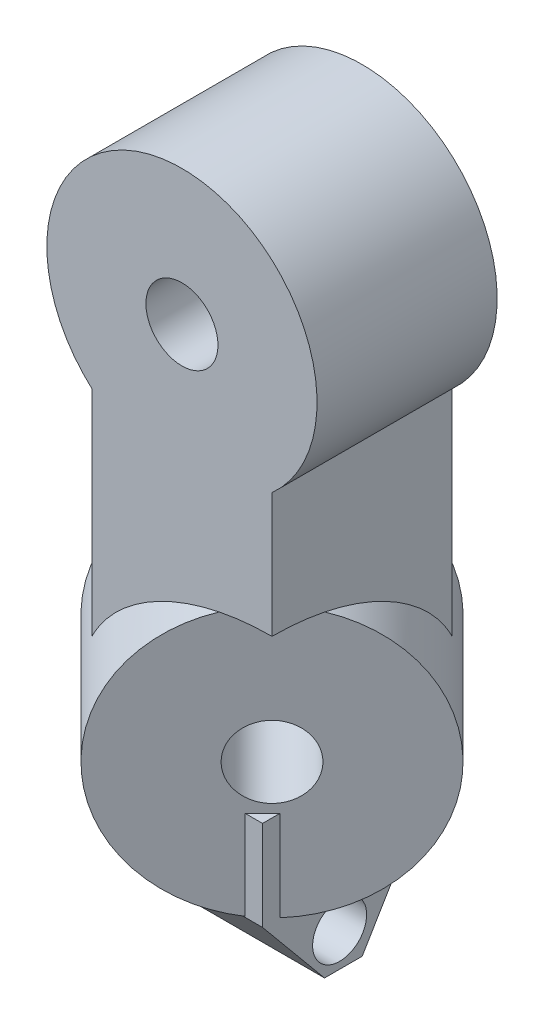
SolidWorks part; units mm, degrees
ref_plane "Front Plane" through (0, 0, 0) normal (0, 0, 1) x (1, 0, 0)
ref_plane "Top Plane" through (0, 0, 0) normal (0, 1, 0) x (1, 0, 0)
ref_plane "Right Plane" through (0, 0, 0) normal (1, 0, 0) x (0, 0, -1)
sketch "Sketch1" plane through (0, 0, 0) normal (0, 0, 1) x (1, 0, 0)
  line L1 (5.0265, -10.0235) -> (-4.9735, -10.0235)
  line L2 (5.0265, -10.0235) -> (5.0265, 4.3863)
  line L4 (-4.9735, -10.0235) -> (-4.9735, 4.3863)
  line L5 (5.0265, -10.0235) -> (-1.3013, 2.5949) construction
  line L6 (1.288, 2.5958) -> (-4.9735, -10.0235) construction
  arc A0 (5.0265, 4.3863) -> (-4.9735, 4.3863) centre (0.0265, 9.9765) ccw
  circle A1 centre (0.0265, 9.9765) radius 1.5
  point P0 (0, 0)
  dimension "D2" = 15
  dimension "D3" = 3
  dimension "D1" = 10
  dimension "D4" = 20
extrude "Boss-Extrude1" add sketch "Sketch1" along normal blind 10
sketch "Sketch2" plane through (0, 0, 0) normal (0, 0, -1) x (-1, 0, 0)
  circle A0 centre (-0.0265, 9.9765) radius 2
  dimension "D1" = 4
extrude "Cut-Extrude1" cut sketch "Sketch2" against normal blind 30 contours A0
ref_plane "Plane1" through (2.5132, 0, 2.5132) normal (-0.7071, 0, -0.7071) x (-0.7071, 0, 0.7071)
sketch "Sketch6" plane through (2.5132, 0, 2.5132) normal (-0.7071, 0, -0.7071) x (-0.7071, 0, 0.7071)
  circle A0 centre (3.5168, -10.0235) radius 7.5
  dimension "D1" = 15
extrude "Boss-Extrude3" add sketch "Sketch6" along normal mid plane 10
sketch "Sketch7" plane through (-1.0223, 0, -1.0223) normal (-0.7071, 0, -0.7071) x (-0.7071, 0, 0.7071)
  line L0 (1.4458, -10.0235) -> (5.5879, -10.0235) construction
  circle A0 centre (3.5168, -10.0235) radius 1.5
  dimension "D1" = 3
extrude "Cut-Extrude4" cut sketch "Sketch7" against normal through all both and the other way through all
sketch "Sketch8" plane through (-1.0223, 0, -1.0223) normal (-0.7071, 0, -0.7071) x (-0.7071, 0, 0.7071)
  circle A0 centre (3.5168, -10.0235) radius 2
  dimension "D1" = 4
extrude "Cut-Extrude5" cut sketch "Sketch8" against normal mid plane 36
sketch "Sketch10" plane through (6.0488, 0, 6.0488) normal (0.7071, 0, 0.7071) x (0.7071, 0, -0.7071)
  circle A0 centre (-3.5168, -10.0235) radius 7.5
extrude "Cut-Extrude7" cut sketch "Sketch10" along normal blind 9
mirror "Mirror1" about plane through (2.5132, 0, 2.5132) normal (-0.7071, 0, -0.7071) of "Cut-Extrude7"
ref_plane "Plane2" through (0, -17.5, 0) normal (0, 1, 0) x (1, 0, 0)
sketch "Sketch11" plane through (0, -17.5, 0) normal (0, 1, 0) x (1, 0, 0)
  line L0 (-5.2768, -10.3033) -> (-2.4735, -7.5) construction
  line L1 (-8.8124, -6.7678) -> (-1.7413, -13.8388) construction
  line L2 (8.8653, -3.2322) -> (1.7942, 3.8388) construction
  line L3 (2.5265, -2.5) -> (5.3298, 0.3033) construction
  line L9 (-4.2197, -1.2792) -> (3.7803, -1.2792)
  line L10 (-4.2197, -1.2792) -> (-4.2197, -9.2792)
  line L11 (-4.2197, -9.2792) -> (3.7803, -9.2792)
  line L12 (3.7803, -1.2792) -> (3.7803, -9.2792)
  line L13 (-4.2197, -1.2792) -> (3.7803, -9.2792) construction
  line L14 (-4.2197, -9.2792) -> (3.7803, -1.2792) construction
  point P6 (-0.2197, -5.2792)
  point P9 (-0.2197, -5.2792)
  dimension "D1" = 8
extrude "Boss-Extrude4" add sketch "Sketch11" along normal mid plane 10
sketch "Sketch13" plane through (3.7803, 0, 0) normal (1, 0, 0) x (0, 0, -1)
  line L0 (0, 17.4765) -> (-10, 17.4765) construction
  line L1 (-10, 17.4765) -> (-5, 17.4765) construction
  line L2 (-5, 17.4765) -> (-5, -22.5) construction
  line L3 (-9.2792, -22.5) -> (-1.2792, -22.5) construction
  line L4 (-9.2792, -17.5) -> (-9.2792, -22.5)
  line L5 (-9.2792, -12.5) -> (-9.2792, -22.5) construction
  line L6 (-9.2792, -22.5) -> (-1.2792, -22.5)
  line L7 (-1.2792, -22.5) -> (-1.2792, -17.519)
  line L8 (-5, -17.5101) -> (-9.2792, -17.5)
  line L9 (-9.2792, -17.5) -> (-5.8369, -21.6536)
  line L10 (-5.8369, -21.6536) -> (-3.7457, -21.6536)
  line L11 (-3.7457, -21.6536) -> (-1.2792, -17.519)
  circle A0 centre (-5, -19.7716) radius 1.5
  line M5 (-1.2792, -22.5) -> (-1.2792, -15.3447)
  line M9 (-9.2792, -12.5) -> (-9.2792, -22.5)
  line M10 (-9.2792, -22.5) -> (-1.2792, -22.5)
  dimension "D1" = 3
extrude "Cut-Extrude8" cut sketch "Sketch13" against normal blind 10 contours A0 | L11 L10 L9 M9 M10 M5
